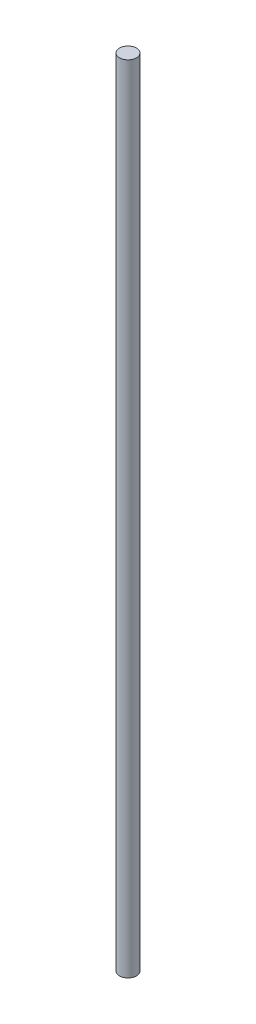
SolidWorks part; units mm, degrees
material "Plain Carbon Steel"
ref_plane "Front Plane" through (0, 0, 0) normal (0, 0, 1) x (1, 0, 0)
ref_plane "Top Plane" through (0, 0, 0) normal (0, 1, 0) x (1, 0, 0)
ref_plane "Right Plane" through (0, 0, 0) normal (1, 0, 0) x (0, 0, -1)
sketch "Sketch1" plane through (0, 0, 0) normal (0, 1, 0) x (1, 0, 0)
  circle A0 centre (0, 0) radius 1.6
  dimension "D1" = 3.2
extrude "Boss-Extrude1" add sketch "Sketch1" along normal blind 150
